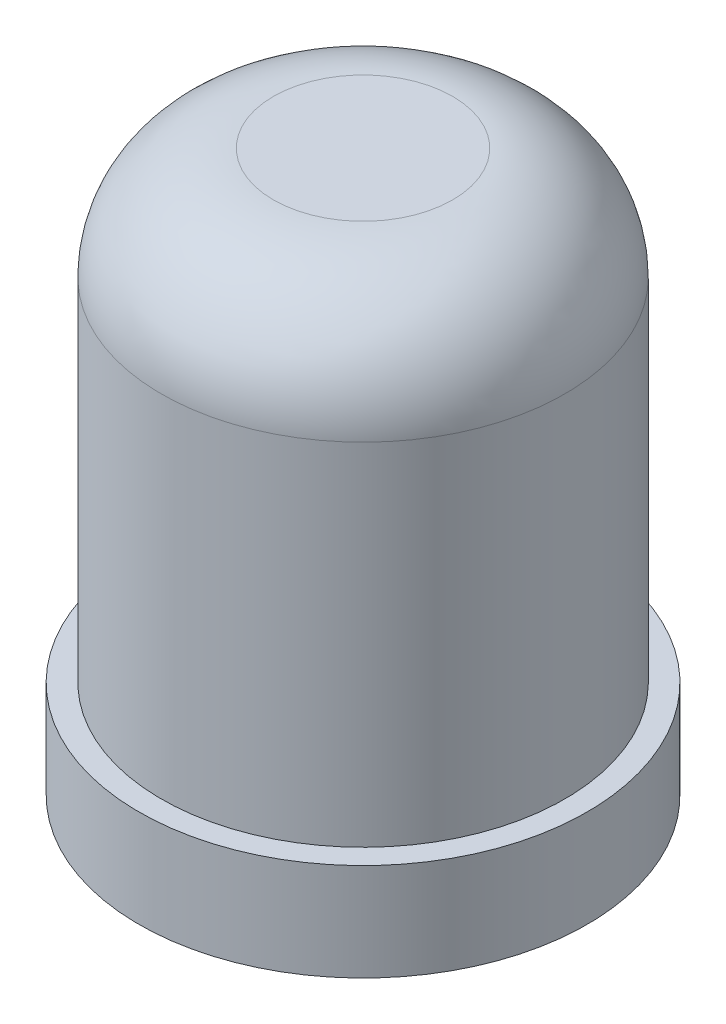
SolidWorks part; units mm, degrees
ref_plane "Ön Düzlem" through (0, 0, 0) normal (0, 0, 1) x (1, 0, 0)
ref_plane "Üst Düzlem" through (0, 0, 0) normal (0, 1, 0) x (1, 0, 0)
ref_plane "Sağ Düzlem" through (0, 0, 0) normal (1, 0, 0) x (0, 0, -1)
sketch "Çizim1" plane through (0, 0, 0) normal (0, 0, 1) x (1, 0, 0)
  line L0 (0, 0) -> (10, 0)
  line L1 (10, 0) -> (10, 4.3466)
  line L2 (10, 4.3466) -> (9, 4.3466)
  line L3 (9, 4.3466) -> (9, 20)
  line L4 (4, 25) -> (0, 25)
  line L5 (0, 25) -> (0, 0)
  arc A0 (4, 25) -> (9, 20) centre (4, 20) cw
  dimension "D2" = 10
  dimension "D1" = 5
  dimension "D3" = 1
  dimension "D4" = 25
revolve "Döndür2" add sketch "Çizim1" angle 360 about L5
